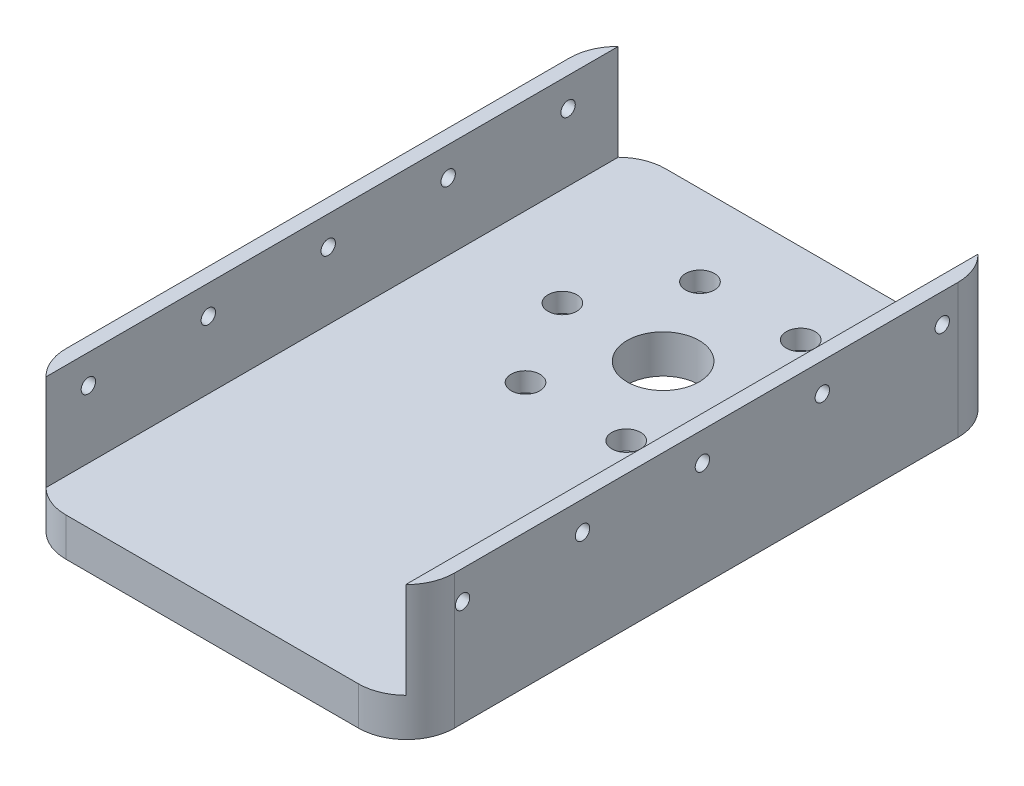
SolidWorks part; units mm, degrees
ref_plane "Front Plane" through (0, 0, 0) normal (0, 0, 1) x (1, 0, 0)
ref_plane "Top Plane" through (0, 0, 0) normal (0, 1, 0) x (1, 0, 0)
ref_plane "Right Plane" through (0, 0, 0) normal (1, 0, 0) x (0, 0, -1)
sketch "Sketch1" plane through (0, 0, 0) normal (0, 1, 0) x (1, 0, 0)
  line L1 (0, 0) -> (78, 0)
  line L2 (0, 0) -> (0, 125)
  line L3 (0, 125) -> (78, 125)
  line L4 (78, 0) -> (78, 125)
  dimension "D1" = 78
  dimension "D2" = 125
extrude "Boss-Extrude1" add sketch "Sketch1" along normal blind 8
sketch "Sketch2" plane through (0, 8, 0) normal (0, 1, 0) x (-1, 0, 0)
  line L0 (-78, -90) -> (-41.5, -90) construction
  line L1 (-78, 0) -> (-78, -125) construction
  line L2 (-41.5, -90) -> (-62.5, -90) construction
  line L3 (-78, -125) -> (-78, -90) construction
  circle A0 centre (-41.5, -90) radius 7.5
  circle A1 centre (-62.5, -90) radius 3
  circle A12 centre (-52, -71.8135) radius 3
  circle A13 centre (-31, -71.8135) radius 3
  circle A14 centre (-20.5, -90) radius 3
  circle A15 centre (-31, -108.1865) radius 3
  circle A16 centre (-52, -108.1865) radius 3
  point P21 (-36, -83.9378)
  point P22 (-40.5, -88.2679)
  point P23 (-41.5, -90)
  dimension "D4" = 15
  dimension "D6" = 6
  dimension "D1" = 36.5
  dimension "D2" = 21
  dimension "D3" = 35
  dimension "D5" = 0
  dimension "D7" = 6
extrude "Cut-Extrude1" cut sketch "Sketch2" against normal blind 4
sketch "Sketch3" plane through (0, 4, 0) normal (0, 1, 0) x (1, 0, 0)
  circle A0 centre (41.5, 90) radius 7.5
  dimension "D1" = 15
extrude "Cut-Extrude2" cut sketch "Sketch3" against normal through all
sketch "Sketch4" plane through (78, 0, 0) normal (1, 0, 0) x (0, 0, -1)
  line L0 (125, 8) -> (125, 0) construction
  line L1 (0, 8) -> (125, 8)
  line L2 (0, 8) -> (0, 28)
  line L3 (0, 28) -> (125, 28)
  line L4 (125, 8) -> (125, 28)
  line L5 (11.6922, 28) -> (11.6922, 22) construction
  circle A0 centre (11.6922, 22) radius 1.5
  circle A1 centre (36.6922, 22) radius 1.5
  circle A2 centre (61.6922, 22) radius 1.5
  circle A3 centre (86.6922, 22) radius 1.5
  circle A4 centre (111.6922, 22) radius 1.5
  dimension "D4" = 3
  dimension "D1" = 20
  dimension "D2" = 0
  dimension "D3" = 6
  dimension "D5" = 5
extrude "Boss-Extrude2" add sketch "Sketch4" against normal blind 3 contours L2 L1 L4 L3
sketch "Sketch5" plane through (0, 8, 0) normal (0, 1, 0) x (-1, 0, 0)
  circle A0 centre (-62.5, -90) radius 1.5
  circle A11 centre (-52, -71.8135) radius 1.5
  circle A12 centre (-31, -71.8135) radius 1.5
  circle A13 centre (-20.5, -90) radius 1.5
  circle A14 centre (-31, -108.1865) radius 1.5
  circle A15 centre (-52, -108.1865) radius 1.5
  point P16 (-36, -96.0622)
  point P17 (-40.5, -91.7321)
  point P18 (-41.5, -90)
  dimension "D1" = 3
  dimension "D2" = 6
extrude "Cut-Extrude3" cut sketch "Sketch5" against normal through all
sketch "Sketch8" plane through (0, 0, 0) normal (-1, 0, 0) x (0, 0, 1)
  line L1 (-125, 0) -> (0, 0)
  line L2 (-125, 0) -> (-125, 28)
  line L3 (-125, 28) -> (0, 28)
  line L4 (0, 0) -> (0, 28)
  dimension "D1" = 28
extrude "Boss-Extrude3" add sketch "Sketch8" along normal blind 3
sketch "Sketch9" plane through (0, 0, 0) normal (1, 0, 0) x (0, 0, -1)
  circle A0 centre (11.6922, 22) radius 1.5
  circle A1 centre (36.6922, 22) radius 1.5
  circle A2 centre (61.6922, 22) radius 1.5
  circle A3 centre (86.6922, 22) radius 1.5
  circle A4 centre (111.6922, 22) radius 1.5
  dimension "D1" = 3
  dimension "D2" = 5
extrude "Cut-Extrude5" cut sketch "Sketch9" against normal through all
fillet "Fillet2" radius 10 4 edges at (-3, 14, -125) (78, 14, -125) (78, 14, 0) (-3, 14, 0)
